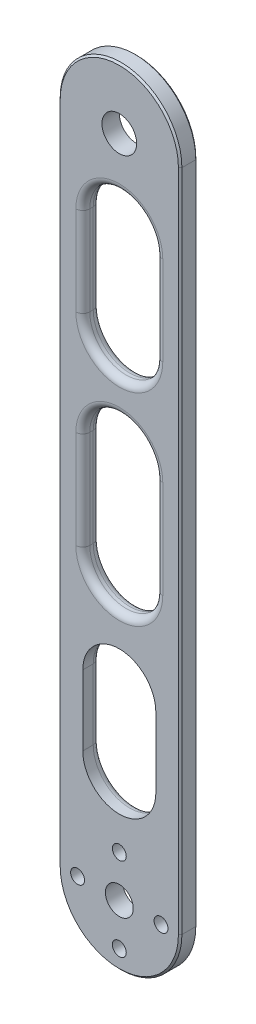
SolidWorks part; units mm, degrees
ref_plane "Front Plane" through (0, 0, 0) normal (0, 0, 1) x (1, 0, 0)
ref_plane "Top Plane" through (0, 0, 0) normal (0, 1, 0) x (1, 0, 0)
ref_plane "Right Plane" through (0, 0, 0) normal (1, 0, 0) x (0, 0, -1)
sketch "Sketch1" plane through (0, 0, 0) normal (0, 0, 1) x (1, 0, 0)
  line L0 (0, 191) -> (0, 0) construction
  line L1 (17.5, 191) -> (17.5, 0)
  line L2 (-17.5, 191) -> (-17.5, 0)
  line L3 (0, 166) -> (0, 140.3487) construction
  line L4 (10.5, 166) -> (10.5, 140.3487)
  line L5 (-10.5, 166) -> (-10.5, 140.3487)
  line L6 (0, 110.3487) -> (0, 82.1797) construction
  line L7 (10.5, 110.3487) -> (10.5, 82.1797)
  line L8 (-10.5, 110.3487) -> (-10.5, 82.1797)
  line L9 (0, 52.1797) -> (0, 32) construction
  line L10 (10.5, 52.1797) -> (10.5, 32)
  line L11 (-10.5, 52.1797) -> (-10.5, 32)
  arc A0 (17.5, 191) -> (-17.5, 191) centre (0, 191) ccw
  arc A1 (-17.5, 0) -> (17.5, 0) centre (0, 0) ccw
  circle A2 centre (0, 0) radius 4
  circle A3 centre (12, 0) radius 2
  circle A4 centre (0, -12) radius 2
  circle A5 centre (-12, 0) radius 2
  circle A6 centre (0, 12) radius 2
  circle A7 centre (0, 191) radius 4.99
  arc A8 (10.5, 166) -> (-10.5, 166) centre (0, 166) ccw
  arc A9 (-10.5, 140.3487) -> (10.5, 140.3487) centre (0, 140.3487) ccw
  arc A10 (10.5, 110.3487) -> (-10.5, 110.3487) centre (0, 110.3487) ccw
  arc A11 (-10.5, 82.1797) -> (10.5, 82.1797) centre (0, 82.1797) ccw
  arc A12 (10.5, 52.1797) -> (-10.5, 52.1797) centre (0, 52.1797) ccw
  arc A13 (-10.5, 32) -> (10.5, 32) centre (0, 32) ccw
  point P3 (0, 95.5)
  point P21 (0, 0)
  point P23 (0, 153.1744)
  point P28 (0, 96.2642)
  point P35 (0, 42.0898)
  dimension "D1" = 8
  dimension "D2" = 17.5
  dimension "D4" = 4
  dimension "D7" = 9.98
  dimension "D3" = 12
  dimension "D6" = 191
  dimension "D8" = 20
  dimension "D9" = 30
  dimension "D10" = 30
  dimension "D11" = 25
  dimension "D12" = 7
  dimension "D13" = 7
  dimension "D14" = 7
  dimension "D5" = 4
extrude "Boss-Extrude1" add sketch "Sketch1" along normal blind 5
fillet "Fillet1" radius 2 4 edges at (10.5, 153.1744, 5) (0, 129.8487, 5) (-10.5, 153.1744, 5) (0, 176.5, 5)
fillet "Fillet2" radius 2 4 edges at (10.5, 153.1744, 0) (0, 129.8487, 0) (-10.5, 153.1744, 0) (0, 176.5, 0)
fillet "Fillet3" radius 2 4 edges at (10.5, 96.2642, 0) (0, 71.6797, 0) (-10.5, 96.2642, 0) (0, 120.8487, 0)
fillet "Fillet4" radius 2 4 edges at (10.5, 96.2642, 5) (0, 71.6797, 5) (-10.5, 96.2642, 5) (0, 120.8487, 5)
fillet "Fillet6" radius 2 4 edges at (10.5, 42.0898, 0) (0, 21.5, 0) (-10.5, 42.0898, 0) (0, 62.6797, 0)
chamfer "Chamfer3" distance 0.5 angle 45 4 edges at (0, -17.5, 0) (17.5, 95.5, 0) (-17.5, 95.5, 0) (0, 208.5, 0)
chamfer "Chamfer4" distance 0.5 angle 45 4 edges at (-17.5, 95.5, 5) (0, -17.5, 5) (0, 208.5, 5) (17.5, 95.5, 5)
